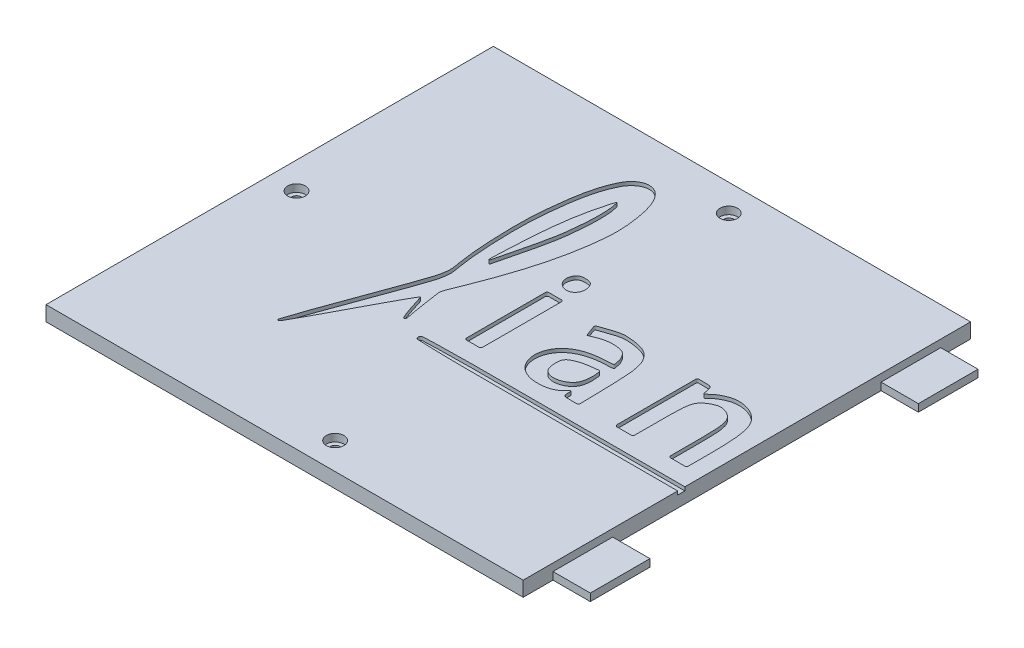
SolidWorks part; units mm, degrees
other "Marca1"
sketch "Croquis4" plane through (-24, 5, 75) normal (0.0144, 0.9293, 0.3691) x (0.9999, -0.0163, 0.0019)
material "PLA"
ref_plane "Alzado" through (0, 0, 0) normal (0, 0, 1) x (1, 0, 0)
ref_plane "Planta" through (0, 0, 0) normal (0, 1, 0) x (1, 0, 0)
ref_plane "Vista lateral" through (0, 0, 0) normal (1, 0, 0) x (0, 0, -1)
sketch "Croquis1" plane through (0, 0, 0) normal (0, 1, 0) x (1, 0, 0)
  line L0 (-327.9437, 75) -> (-327.9437, -75)
  line L1 (-327.9437, 75) -> (-27.9437, 75)
  line L2 (-27.9437, 75) -> (-24, 71.0563)
  line L3 (-327.9437, -75) -> (-27.9437, -75)
  line L4 (-27.9437, -75) -> (-24, -71.0563)
  circle A0 centre (0, 0) radius 75 construction
  arc A1 (-24, 71.0563) -> (-24, -71.0563) centre (0, 0) ccw
  point P6 (-327.9437, 0)
  point P11 (-75, 0)
  dimension "D1" = 150
  dimension "D2" = 150
  dimension "D3" = 300
  dimension "D4" = 135
  dimension "D5" = 24
extrude "Saliente-Extruir1" add sketch "Croquis1" along normal blind 5 contours L1 L2 A1 L4 L3 L0
sketch "Croquis2" plane through (0, 5, 0) normal (0, 1, 0) x (1, 0, 0)
  line L0 (-327.9437, 75) -> (-27.9437, 75) construction
  line L1 (-327.9437, -75) -> (-27.9437, -75) construction
  line L2 (-327.9437, 75) -> (-327.9437, -75) construction
  circle A0 centre (-318.9437, 0) radius 1.6
  circle A1 centre (-240.0037, 66) radius 1.6
  circle A2 centre (-240.0037, -66) radius 1.6
  circle A3 centre (-80.0037, -66) radius 1.6
  circle A4 centre (-80.0037, 66) radius 1.6
  dimension "D1" = 3.2
  dimension "D2" = 9
  dimension "D3" = 9
  dimension "D4" = 9
  dimension "D5" = 160
  dimension "D6" = 87.94
extrude "Cortar-Extruir1" cut sketch "Croquis2" against normal blind 5
sketch "Croquis3" plane through (0, 5, 0) normal (0, 1, 0) x (1, 0, 0)
  circle A0 centre (-240.0037, -66) radius 2.95
  circle A1 centre (-80.0037, -66) radius 2.95
  circle A2 centre (-80.0037, 66) radius 2.95
  circle A3 centre (-240.0037, 66) radius 2.95
  circle A4 centre (-318.9437, 0) radius 2.95
  dimension "D1" = 5.9
extrude "Cortar-Extruir2" cut sketch "Croquis3" against normal blind 2.5
sketch "Croquis5" plane through (0, 5, 0) normal (0, 1, 0) x (1, 0, 0)
  spline S0 degree 3 number of poles 565 (-264.8912, -10.407) -> (-264.8912, -10.407)
  spline S1 degree 3 number of poles 279 (-262.6484, 48.2089) -> (-262.6484, 48.2089)
  spline S2 degree 3 number of poles 493 (-213.5311, -14.7576) -> (-213.5311, -14.7576)
  spline S3 degree 3 number of poles 157 (-225.2653, -4.52) -> (-225.2653, -4.52)
  spline S4 degree 3 number of poles 343 (-98.8163, -23.8618) -> (-98.8163, -23.8618)
  spline S5 degree 3 number of poles 343 (-189.9262, 10.8546) -> (-189.9262, 10.8546)
  spline S6 degree 3 number of poles 380 (-145.717, -14.6405) -> (-145.717, -14.6405)
  spline S7 degree 3 number of poles 125 (-156.8594, -5.2926) -> (-156.8594, -5.2926)
  spline S8 degree 3 number of poles 123 (-242.4618, 21.9905) -> (-242.4618, 21.9905)
  spline S9 degree 3 poles (-242.3565, -0.9911) (-242.3565, 3.3839) (-242.3565, 7.7589) (-242.3565, 12.1339) (-242.3565, 12.24) (-242.3565, 12.4521) (-242.7133, 12.8089) (-242.9254, 12.8089) (-243.0315, 12.8089) (-243.7065, 12.8089) (-244.3815, 12.8089) (-245.0565, 12.8089) (-245.7315, 12.8089) (-246.4065, 12.8089) (-247.0815, 12.8089) (-247.1876, 12.8089) (-247.3997, 12.8089) (-247.7565, 12.4521) (-247.7565, 12.24) (-247.7565, 12.1339) (-247.7565, 7.7589) (-247.7565, 3.3839) (-247.7565, -0.9911) (-247.7565, -5.3661) (-247.7565, -9.7411) (-247.7565, -14.1161) (-247.7565, -14.2221) (-247.7565, -14.4343) (-247.3997, -14.7911) (-247.1876, -14.7911) (-247.0815, -14.7911) (-246.4065, -14.7911) (-245.7315, -14.7911) (-245.0565, -14.7911) (-244.3815, -14.7911) (-243.7065, -14.7911) (-243.0315, -14.7911) (-242.9254, -14.7911) (-242.7133, -14.7911) (-242.3565, -14.4343) (-242.3565, -14.2221) (-242.3565, -14.1161) (-242.3565, -9.7411) (-242.3565, -5.3661) (-242.3565, -0.9911) (-242.3565, 3.3839) (-242.3565, 7.7589) knots -0.203746 0 0 0 0.203746 0.203746 0.203746 0.208686 0.213625 0.218565 0.218565 0.218565 0.25 0.25 0.25 0.281435 0.281435 0.281435 0.286375 0.291314 0.296254 0.296254 0.296254 0.5 0.5 0.5 0.703746 0.703746 0.703746 0.708686 0.713625 0.718565 0.718565 0.718565 0.75 0.75 0.75 0.781435 0.781435 0.781435 0.786375 0.791314 0.796254 0.796254 0.796254 1 1 1 1.203746 1.203746 1.203746 only from (-242.3565, -0.9911) to (-242.3565, -0.9911)
  spline S10 degree 3 number of poles 99 (-100.9338, -21.7323) -> (-100.9338, -21.7323)
extrude "Cortar-Extruir3" cut sketch "Croquis5" against normal blind 1.2
sketch "Croquis6" plane through (0, 5, 0) normal (0, 1, 0) x (1, 0, 0)
  line L0 (-327.9437, 75) -> (-327.9437, -75) construction
  line L1 (-167.9437, -104.5928) -> (32.0563, -104.5928)
  line L2 (-167.9437, -104.5928) -> (-167.9437, 95.4072)
  line L3 (-167.9437, 95.4072) -> (32.0563, 95.4072)
  line L4 (32.0563, -104.5928) -> (32.0563, 95.4072)
  line L5 (-167.9437, -104.5928) -> (32.0563, 95.4072) construction
  line L6 (-167.9437, 95.4072) -> (32.0563, -104.5928) construction
  point P0 (-67.9437, -4.5928)
  dimension "D1" = 160
  dimension "D2" = 200
  dimension "D3" = 200
extrude "Cortar-Extruir4" cut sketch "Croquis6" against normal blind 10
sketch "Croquis7" plane through (0, 0, 0) normal (0, -1, 0) x (1, 0, 0)
  line L0 (-167.9437, -75) -> (-167.9437, 75) construction
  line L1 (-180.4437, 65) -> (-155.4437, 65)
  line L2 (-180.4437, 65) -> (-180.4437, 45)
  line L3 (-180.4437, 45) -> (-155.4437, 45)
  line L4 (-155.4437, 65) -> (-155.4437, 45)
  line L5 (-180.4437, 65) -> (-155.4437, 45) construction
  line L6 (-180.4437, 45) -> (-155.4437, 65) construction
  line L7 (-327.9437, 75) -> (-167.9437, 75) construction
  line L8 (-180.4437, -45) -> (-155.4437, -45)
  line L9 (-180.4437, -45) -> (-180.4437, -65)
  line L10 (-180.4437, -65) -> (-155.4437, -65)
  line L11 (-155.4437, -45) -> (-155.4437, -65)
  line L12 (-180.4437, -45) -> (-155.4437, -65) construction
  line L13 (-180.4437, -65) -> (-155.4437, -45) construction
  line L15 (-327.9437, -75) -> (-167.9437, -75) construction
  point P0 (-167.9437, 55)
  point P7 (-167.9437, -55)
  dimension "D1" = 20
  dimension "D2" = 10
  dimension "D3" = 25
  dimension "D4" = 10
extrude "Saliente-Extruir2" add sketch "Croquis7" against normal blind 2.5
